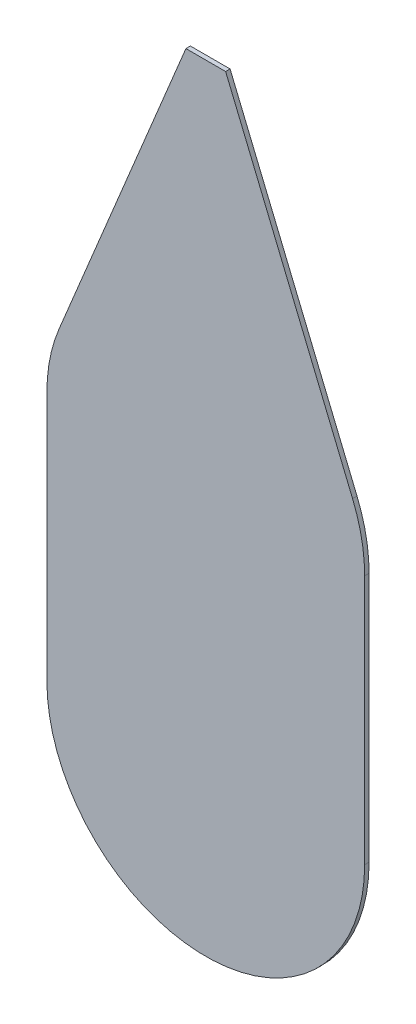
SolidWorks part; units mm, degrees
ref_plane "Front Plane" through (0, 0, 0) normal (0, 0, 1) x (1, 0, 0)
ref_plane "Top Plane" through (0, 0, 0) normal (0, 1, 0) x (1, 0, 0)
ref_plane "Right Plane" through (0, 0, 0) normal (1, 0, 0) x (0, 0, -1)
sketch "Sketch1" plane through (0, 0, 0) normal (0, 0, 1) x (1, 0, 0)
  line L5 (28.4665, 5.1614) -> (28.4665, 15.1614)
  line L6 (15.7665, 5.1614) -> (15.7665, 15.1614)
  line L7 (21.3228, 29.8384) -> (16.2499, 17.5914)
  line L8 (22.9103, 29.8384) -> (27.9831, 17.5914)
  line L9 (22.9103, 29.8384) -> (21.3228, 29.8384)
  arc A3 (15.7665, 5.1614) -> (28.4665, 5.1614) centre (22.1165, 5.1614) ccw
  arc A4 (28.4665, 15.1614) -> (27.9831, 17.5914) centre (22.1165, 15.1614) ccw
  arc A5 (16.2499, 17.5914) -> (15.7665, 15.1614) centre (22.1165, 15.1614) ccw
extrude "Boss-Extrude2" add sketch "Sketch1" against normal blind 0.1778
